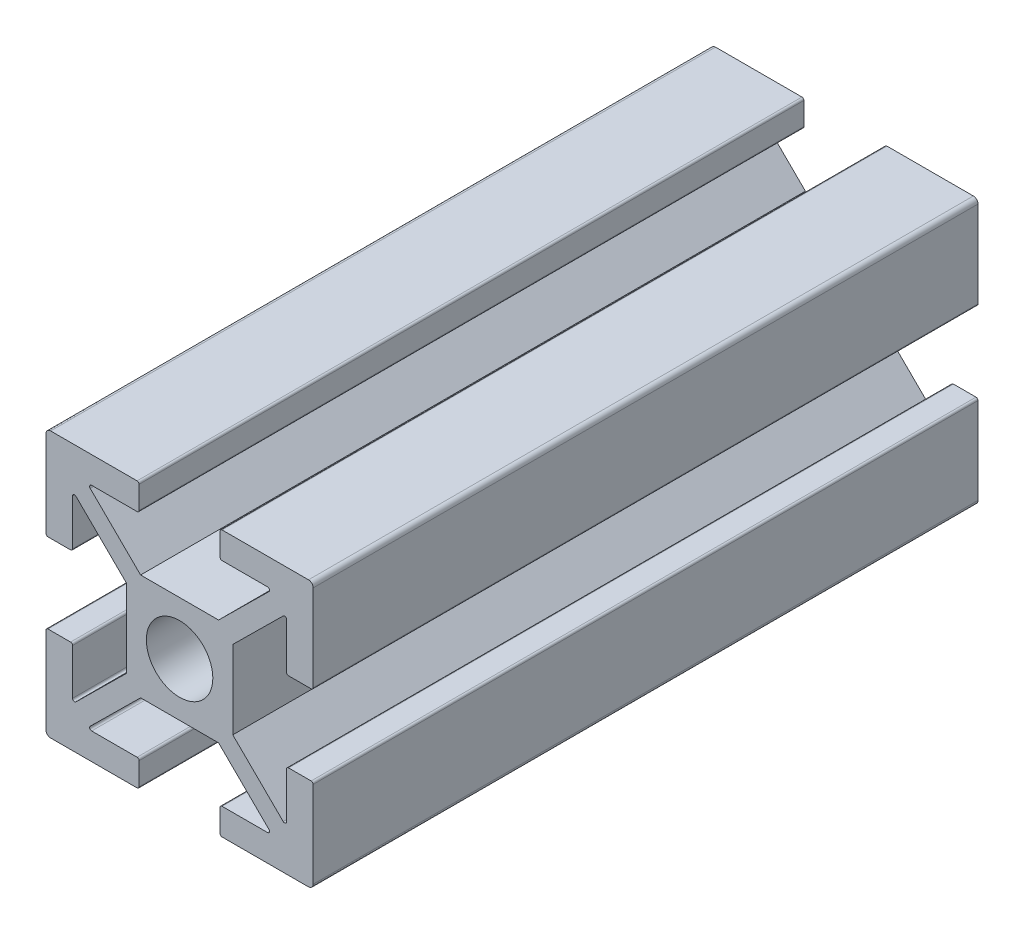
SolidWorks part; units mm, degrees
ref_plane "Front Plane" through (0, 0, 0) normal (0, 0, 1) x (1, 0, 0)
ref_plane "Top Plane" through (0, 0, 0) normal (0, 1, 0) x (1, 0, 0)
ref_plane "Right Plane" through (0, 0, 0) normal (1, 0, 0) x (0, 0, -1)
sketch "Sketch1" plane through (0, 0, 0) normal (0, 0, 1) x (1, 0, 0)
  line L0 (-31.3764, -0.0618) -> (-29.6764, -0.0618)
  line L1 (-24.6764, 6.9382) -> (-31.1764, 6.9382)
  line L2 (-31.5264, 0.0882) -> (-31.5264, 6.5882)
  line L3 (-18.5469, 0.9382) -> (-24.4133, 0.9382)
  line L4 (-25.4801, -6.0072) -> (-25.4801, -0.1164)
  line L5 (-29.5264, 0.0882) -> (-29.5264, 3.5244)
  line L6 (-28.0945, 4.9382) -> (-24.6764, 4.9382)
  line L7 (-24.5264, 5.0882) -> (-24.5264, 6.7882)
  line L8 (-29.5264, 4.9382) -> (-25.4801, 0.9382) construction
  line L9 (-29.271, 3.631) -> (-25.4801, -0.1164)
  line L10 (-28.1999, 4.6815) -> (-24.4133, 0.9382)
  line L11 (-13.4338, 4.9382) -> (-17.4801, 0.9382) construction
  line L12 (-21.4801, -3.0618) -> (-21.4801, 8.6268) construction
  line L13 (-21.4801, -3.0618) -> (-36.4642, -3.0618) construction
  line L14 (-14.7603, 4.6815) -> (-18.5469, 0.9382)
  line L15 (-13.6893, 3.631) -> (-17.4801, -0.1164)
  line L16 (-18.4338, 5.0882) -> (-18.4338, 6.7882)
  line L17 (-14.8657, 4.9382) -> (-18.2838, 4.9382)
  line L18 (-13.4338, 0.0882) -> (-13.4338, 3.5244)
  line L19 (-17.4801, -6.0072) -> (-17.4801, -0.1164)
  line L20 (-11.4338, 0.0882) -> (-11.4338, 6.5882)
  line L21 (-18.2838, 6.9382) -> (-11.7838, 6.9382)
  line L22 (-11.5838, -0.0618) -> (-13.2838, -0.0618)
  line L23 (-13.4338, -11.0618) -> (-17.4801, -7.0618) construction
  line L24 (-29.5264, -11.0618) -> (-25.4801, -7.0618) construction
  line L25 (-11.5838, -6.0618) -> (-13.2838, -6.0618)
  line L26 (-18.2838, -13.0618) -> (-11.7838, -13.0618)
  line L27 (-11.4338, -6.2118) -> (-11.4338, -12.7118)
  line L28 (-13.4338, -6.2118) -> (-13.4338, -9.648)
  line L29 (-14.8657, -11.0618) -> (-18.2838, -11.0618)
  line L30 (-18.4338, -11.2118) -> (-18.4338, -12.9118)
  line L31 (-13.6893, -9.7547) -> (-17.4801, -6.0072)
  line L32 (-14.7603, -10.8051) -> (-18.5469, -7.0618)
  line L33 (-28.1999, -10.8051) -> (-24.4133, -7.0618)
  line L34 (-29.271, -9.7547) -> (-25.4801, -6.0072)
  line L35 (-24.5264, -11.2118) -> (-24.5264, -12.9118)
  line L36 (-28.0945, -11.0618) -> (-24.6764, -11.0618)
  line L37 (-29.5264, -6.2118) -> (-29.5264, -9.648)
  line L38 (-18.5469, -7.0618) -> (-24.4133, -7.0618)
  line L39 (-31.5264, -6.2118) -> (-31.5264, -12.7118)
  line L40 (-24.6764, -13.0618) -> (-31.1764, -13.0618)
  line L41 (-31.3764, -6.0618) -> (-29.6764, -6.0618)
  circle A0 centre (-21.4801, -3.0618) radius 2.5
  arc A1 (-31.5264, 6.5882) -> (-31.1764, 6.9382) centre (-31.1764, 6.5882) cw
  arc A2 (-31.3764, -0.0618) -> (-31.5264, 0.0882) centre (-31.3764, 0.0882) cw
  arc A3 (-29.6764, -0.0618) -> (-29.5264, 0.0882) centre (-29.6764, 0.0882) ccw
  arc A4 (-24.6764, 6.9382) -> (-24.5264, 6.7882) centre (-24.6764, 6.7882) cw
  arc A5 (-24.6764, 4.9382) -> (-24.5264, 5.0882) centre (-24.6764, 5.0882) ccw
  arc A6 (-28.1999, 4.6815) -> (-28.0945, 4.9382) centre (-28.0945, 4.7882) cw
  arc A7 (-29.271, 3.631) -> (-29.5264, 3.5244) centre (-29.3764, 3.5244) ccw
  arc A8 (-13.6893, 3.631) -> (-13.4338, 3.5244) centre (-13.5838, 3.5244) cw
  arc A9 (-14.7603, 4.6815) -> (-14.8657, 4.9382) centre (-14.8657, 4.7882) ccw
  arc A10 (-18.2838, 4.9382) -> (-18.4338, 5.0882) centre (-18.2838, 5.0882) cw
  arc A11 (-18.2838, 6.9382) -> (-18.4338, 6.7882) centre (-18.2838, 6.7882) ccw
  arc A12 (-13.2838, -0.0618) -> (-13.4338, 0.0882) centre (-13.2838, 0.0882) cw
  arc A13 (-11.5838, -0.0618) -> (-11.4338, 0.0882) centre (-11.5838, 0.0882) ccw
  arc A14 (-11.4338, 6.5882) -> (-11.7838, 6.9382) centre (-11.7838, 6.5882) ccw
  arc A15 (-11.4338, -12.7118) -> (-11.7838, -13.0618) centre (-11.7838, -12.7118) cw
  arc A16 (-11.5838, -6.0618) -> (-11.4338, -6.2118) centre (-11.5838, -6.2118) cw
  arc A17 (-13.2838, -6.0618) -> (-13.4338, -6.2118) centre (-13.2838, -6.2118) ccw
  arc A18 (-18.2838, -13.0618) -> (-18.4338, -12.9118) centre (-18.2838, -12.9118) cw
  arc A19 (-18.2838, -11.0618) -> (-18.4338, -11.2118) centre (-18.2838, -11.2118) ccw
  arc A20 (-14.7603, -10.8051) -> (-14.8657, -11.0618) centre (-14.8657, -10.9118) cw
  arc A21 (-13.6893, -9.7547) -> (-13.4338, -9.648) centre (-13.5838, -9.648) ccw
  arc A22 (-29.271, -9.7547) -> (-29.5264, -9.648) centre (-29.3764, -9.648) cw
  arc A23 (-28.1999, -10.8051) -> (-28.0945, -11.0618) centre (-28.0945, -10.9118) ccw
  arc A24 (-24.6764, -11.0618) -> (-24.5264, -11.2118) centre (-24.6764, -11.2118) cw
  arc A25 (-24.6764, -13.0618) -> (-24.5264, -12.9118) centre (-24.6764, -12.9118) ccw
  arc A26 (-29.6764, -6.0618) -> (-29.5264, -6.2118) centre (-29.6764, -6.2118) cw
  arc A27 (-31.3764, -6.0618) -> (-31.5264, -6.2118) centre (-31.3764, -6.2118) ccw
  arc A28 (-31.5264, -12.7118) -> (-31.1764, -13.0618) centre (-31.1764, -12.7118) ccw
  point P27 (-18.4338, 4.9382)
  point P28 (-11.4338, -13.0618)
  point P47 (-17.4801, -3.0618)
  point P57 (-21.4801, 0.9382)
  point P59 (-18.4338, 6.9382)
  point P60 (-13.4338, -0.0618)
  point P61 (-11.4338, -0.0618)
  point P62 (-11.4338, 6.9382)
  point P112 (-25.4801, -3.0618)
  point P113 (-11.4338, -6.0618)
  point P114 (-13.4338, -6.0618)
  point P115 (-18.4338, -13.0618)
  point P116 (-21.4801, -7.0618)
  point P117 (-24.5264, -11.0618)
  point P118 (-24.5264, -13.0618)
  point P119 (-29.5264, -6.0618)
  point P120 (-18.4338, -11.0618)
  point P121 (-31.5264, -6.0618)
  point P122 (-31.5264, -13.0618)
  dimension "D3" = 0.35
  dimension "D4" = 0.15
  dimension "D5" = 0.15
  dimension "D6" = 0.15
  dimension "D7" = 0.15
  dimension "D8" = 0.15
  dimension "D9" = 0.15
  dimension "D1" = 0.75
  dimension "D2" = 0.75
extrude "Boss-Extrude1" add sketch "Sketch1" along normal blind 50
